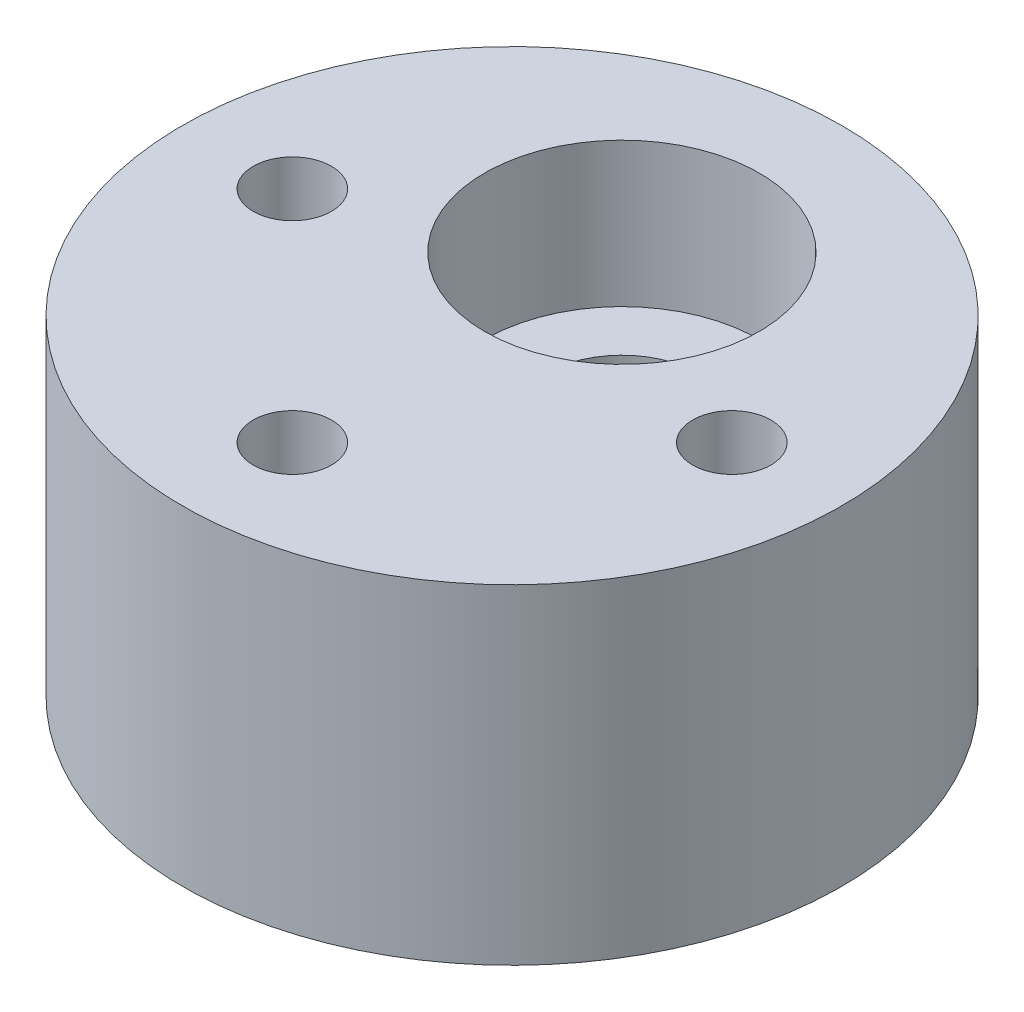
SolidWorks part; units mm, degrees
ref_plane "Front Plane" through (0, 0, 0) normal (0, 0, 1) x (1, 0, 0)
ref_plane "Top Plane" through (0, 0, 0) normal (0, 1, 0) x (1, 0, 0)
ref_plane "Right Plane" through (0, 0, 0) normal (1, 0, 0) x (0, 0, -1)
sketch "Sketch1" plane through (0, 0, 0) normal (0, 1, 0) x (1, 0, 0)
  circle A0 centre (0, 0) radius 9.525
  dimension "D1" = 19.05
extrude "Boss-Extrude1" add sketch "Sketch1" along normal blind 9.525
hole_wizard "CBORE for #8 Socket Head Cap Screw1" positions "Sketch2" profile "Sketch4" counterbore size "#8" standard "ANSI Inch" end condition through all
sketch "Sketch2" plane through (0, 9.525, 0) normal (0, 1, 0) x (1, 0, 0)
  point P0 (0, 3.175)
  dimension "D1" = 3.175
sketch "Sketch4" plane through (0, 9.525, -3.175) normal (1, 0, 0) x (0, 0, 1)
  line L0 (0, 0) -> (0, 9.525)
  line L1 (0, 9.525) -> (2.2479, 9.525)
  line L3 (2.2479, 9.525) -> (2.2479, 4.1656)
  line L4 (2.2479, 4.1656) -> (3.9688, 4.1656)
  line L5 (3.9688, 4.1656) -> (3.9688, 0)
  line L7 (3.9688, 0) -> (0, 0)
  line L11 (0, -6.35) -> (0, 107.95) construction
  dimension "Thru Hole Dia." = 4.4958
  dimension "Thru Hole Depth" = 9.525
  dimension "C'Bore Dia." = 7.9375
  dimension "C'Bore Depth" = 4.1656
hole_wizard "1/16 (0.0625) Diameter Hole1" positions "3DSketch1" profile "Sketch7" hole size "1/16" standard "ANSI Inch"
sketch3d "3DSketch1"
  line L0 (0, 0, -3.175) -> (0, 5.3594, -3.175) construction
  circle A1 centre (0, 0, -3.175) radius 4.7625 construction
  point P0 (0, 0, 0.381)
  point P10 (0, 4.7625, -3.175)
  dimension "D2" = 9.525
  dimension "D1" = 3.556
sketch "Sketch7" plane through (0, 0, 0.381) normal (1, 0, 0) x (0, 0, -1)
  line L0 (0, 0) -> (0, 5.3029)
  line L1 (0, 5.3029) -> (0.7937, 4.826)
  line L2 (0.7937, 4.826) -> (0.7937, 0)
  line L5 (0.7937, 0) -> (0, 0)
  line L10 (0, 5.3029) -> (-0.7938, 4.826) construction
  line L11 (0, -6.35) -> (0, 107.95) construction
  dimension "Hole Dia." = 1.5875
  dimension "Hole Depth" = 4.826
  dimension "Drill Angle" = 118
hole_wizard "#4-40 Tapped Hole1" positions "3DSketch2" profile "Sketch8" tap size "#4-40" standard "ANSI Inch"
sketch3d "3DSketch2"
  circle A0 centre (0, 9.525, 0) radius 9.525 construction
  circle A1 centre (0, 9.525, 0) radius 9.525 construction
  circle A3 centre (0, 9.525, 0) radius 6.35 construction
  point P0 (-6.35, 9.525, 0)
  point P2 (6.35, 9.525, 0)
  point P4 (0, 9.525, 6.35)
  point P11 (0, 19.05, 0)
  point P13 (0, 19.05, 0)
  point P21 (0, 15.875, 0)
  dimension "D1" = 12.7
cosmetic thread "Hole Thread1" parameters "D1"=6.35, "D2"=2.8448
cosmetic thread "Hole Thread2" parameters "D1"=6.35, "D2"=2.8448
cosmetic thread "Hole Thread3" parameters "D1"=6.35, "D2"=2.8448
sketch "Sketch8" plane through (-6.35, 9.525, 0) normal (1, 0, 0) x (0, 0, 1)
  line L0 (0, 0) -> (0, 7.0292)
  line L1 (0, 7.0292) -> (1.1303, 6.35)
  line L2 (1.1303, 6.35) -> (1.1303, 0)
  line L5 (1.1303, 0) -> (0, 0)
  line L10 (0, 7.0292) -> (-1.1303, 6.35) construction
  line L11 (0, -6.35) -> (0, 107.95) construction
  dimension "Tap Drill Dia." = 2.2606
  dimension "Tap Drill Depth" = 6.35
  dimension "Drill Angle" = 118
